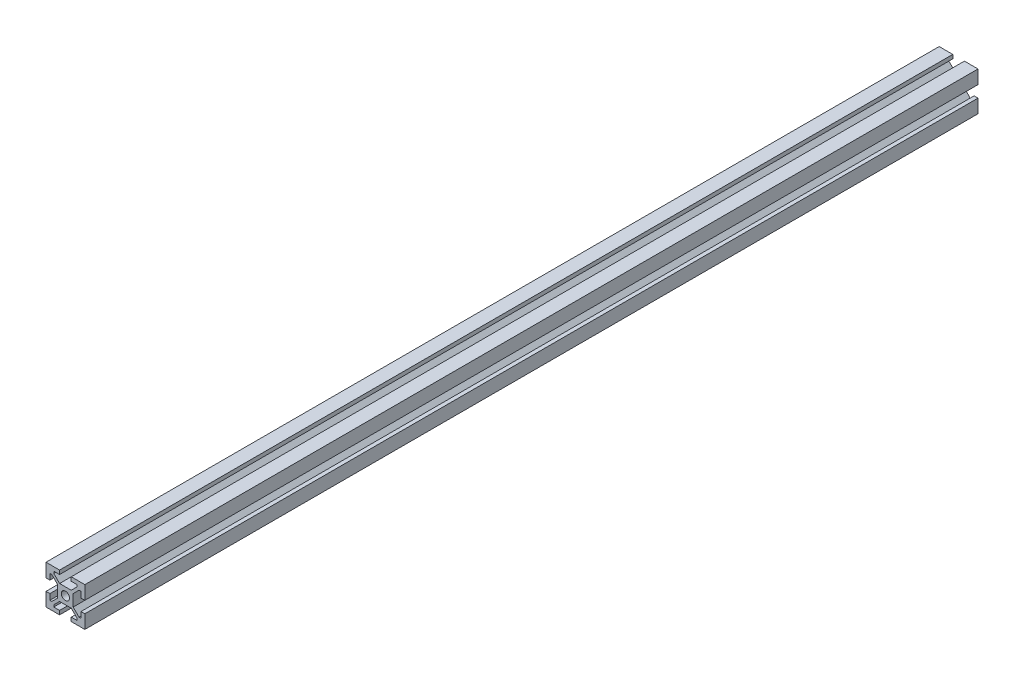
SolidWorks part; units mm, degrees
ref_plane "正面" through (0, 0, 0) normal (0, 0, 1) x (1, 0, 0)
ref_plane "平面" through (0, 0, 0) normal (0, 1, 0) x (1, 0, 0)
ref_plane "右側面" through (0, 0, 0) normal (1, 0, 0) x (0, 0, -1)
sketch "ｽｹｯﾁ2" plane through (0, 0, 0) normal (0, 0, 1) x (1, 0, 0)
  line L0 (0, 0) -> (0, 10) construction
  line L1 (-10, -10) -> (10, -10) construction
  line L2 (-10, -10) -> (-10, 10) construction
  line L3 (-10, 10) -> (10, 10) construction
  line L4 (10, -10) -> (10, 10) construction
  line L5 (-10, -10) -> (10, 10) construction
  line L6 (-10, 10) -> (10, -10) construction
  line L8 (3, 4) -> (-3, 4)
  line L9 (-6, 7) -> (6, 7) construction
  line L10 (-6, 8) -> (-6, 7)
  line L11 (6, 8) -> (6, 7)
  line L12 (-6, 7) -> (-3, 4)
  line L13 (3, 4) -> (6, 7)
  line L14 (-6, 8) -> (-3, 8)
  line L15 (-3, 8) -> (-3, 10)
  line L16 (-3, 10) -> (-10, 10)
  line L17 (6, 8) -> (3, 8)
  line L18 (3, 8) -> (3, 10)
  line L19 (3, 10) -> (10, 10)
  line L20 (7, 6) -> (4, 3)
  line L21 (4, -3) -> (4, 3)
  line L22 (4, -3) -> (7, -6)
  line L23 (8, -6) -> (8, -3)
  line L24 (8, -6) -> (7, -6)
  line L25 (8, -3) -> (10, -3)
  line L26 (10, -3) -> (10, -10)
  line L27 (8, 3) -> (10, 3)
  line L28 (10, 3) -> (10, 10)
  line L29 (8, 6) -> (8, 3)
  line L30 (8, 6) -> (7, 6)
  line L31 (6, -7) -> (3, -4)
  line L32 (-3, -4) -> (3, -4)
  line L33 (-3, -4) -> (-6, -7)
  line L34 (-6, -8) -> (-3, -8)
  line L35 (-6, -8) -> (-6, -7)
  line L36 (-3, -8) -> (-3, -10)
  line L37 (-3, -10) -> (-10, -10)
  line L38 (3, -8) -> (3, -10)
  line L39 (3, -10) -> (10, -10)
  line L40 (6, -8) -> (3, -8)
  line L41 (6, -8) -> (6, -7)
  line L42 (-7, -6) -> (-4, -3)
  line L43 (-4, 3) -> (-4, -3)
  line L44 (-4, 3) -> (-7, 6)
  line L45 (-8, 6) -> (-8, 3)
  line L46 (-8, 6) -> (-7, 6)
  line L47 (-8, 3) -> (-10, 3)
  line L48 (-10, 3) -> (-10, 10)
  line L49 (-8, -3) -> (-10, -3)
  line L50 (-10, -3) -> (-10, -10)
  line L51 (-8, -6) -> (-8, -3)
  line L52 (-8, -6) -> (-7, -6)
  circle A0 centre (0, 0) radius 2.1
  point P0 (0, 0)
  point P11 (0, 10)
  point P14 (0, 4)
  point P17 (0, 7)
  dimension "D8" = 4.2
  dimension "D1" = 20
  dimension "D2" = 6
  dimension "D3" = 2
  dimension "D4" = 4
  dimension "D5" = 12
  dimension "D6" = 6
  dimension "D7" = 4
extrude "ﾎﾞｽ - 押し出し1" add sketch "ｽｹｯﾁ2" along normal blind 460
